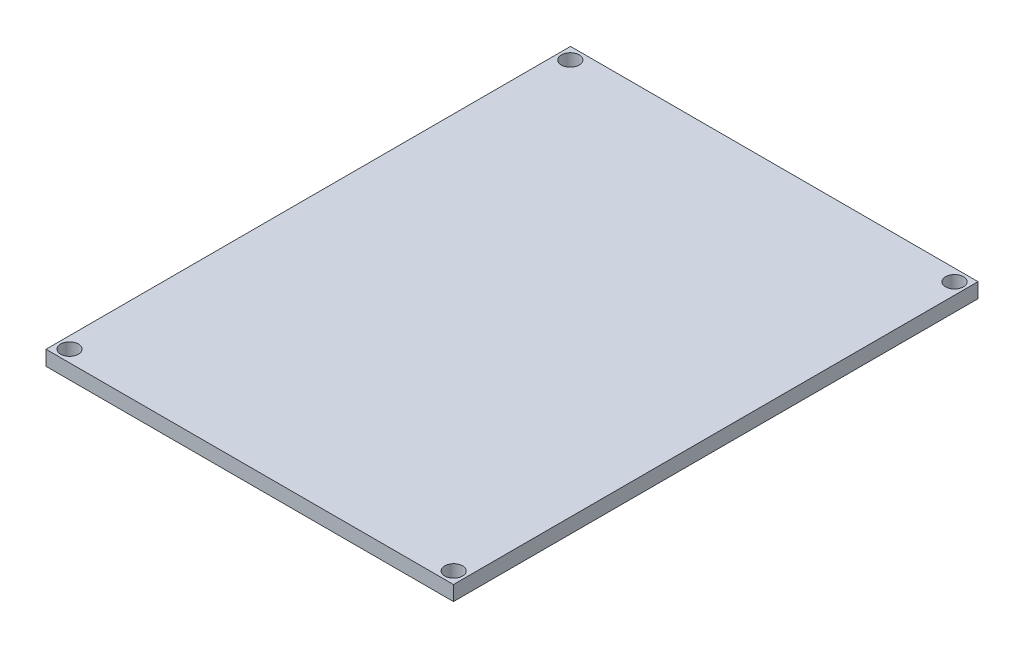
SolidWorks part; units mm, degrees
material "Silicon"
ref_plane "Front Plane" through (0, 0, 0) normal (0, 0, 1) x (1, 0, 0)
ref_plane "Top Plane" through (0, 0, 0) normal (0, 1, 0) x (1, 0, 0)
ref_plane "Right Plane" through (0, 0, 0) normal (1, 0, 0) x (0, 0, -1)
sketch "Sketch1" plane through (0, 0, 0) normal (0, 1, 0) x (1, 0, 0)
  line L1 (-34.925, -44.958) -> (34.925, -44.958)
  line L2 (-34.925, -44.958) -> (-34.925, 44.958)
  line L3 (-34.925, 44.958) -> (34.925, 44.958)
  line L4 (34.925, -44.958) -> (34.925, 44.958)
  line L5 (-34.925, -44.958) -> (34.925, 44.958) construction
  line L6 (-34.925, 44.958) -> (34.925, -44.958) construction
  point P0 (0, 0)
  dimension "D1" = 89.916
  dimension "D2" = 69.85
extrude "Boss-Extrude1" add sketch "Sketch1" along normal mid plane 2.54
sketch "Sketch2" plane through (0, 1.27, 0) normal (0, 1, 0) x (1, 0, 0)
  line L3 (-32.9311, 42.926) -> (32.9311, 42.926) construction
  line L4 (-32.9311, 42.926) -> (-32.9311, -42.926) construction
  line L5 (-32.9311, -42.926) -> (32.9311, -42.926) construction
  line L6 (32.9311, 42.926) -> (32.9311, -42.926) construction
  line L7 (-32.9311, 42.926) -> (32.9311, -42.926) construction
  line L8 (-32.9311, -42.926) -> (32.9311, 42.926) construction
  circle A4 centre (-32.9311, 42.926) radius 1.524
  circle A5 centre (32.9311, 42.926) radius 1.524
  circle A6 centre (32.9311, -42.926) radius 1.524
  circle A7 centre (-32.9311, -42.926) radius 1.524
  point P0 (0, 0)
  dimension "D3" = 3.048
  dimension "D1" = 85.852
  dimension "D2" = 65.8622
extrude "Cut-Extrude1" cut sketch "Sketch2" against normal up to next
